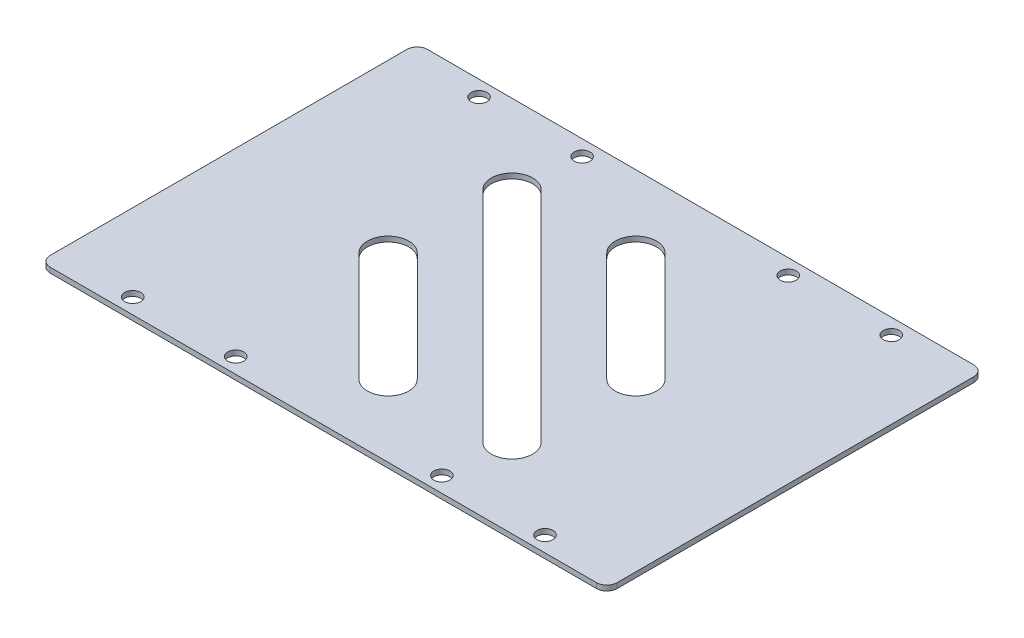
SolidWorks part; units mm, degrees
material "Thornel Mat VMA"
ref_plane "前视基准面" through (0, 0, 0) normal (0, 0, 1) x (1, 0, 0)
ref_plane "上视基准面" through (0, 0, 0) normal (0, 1, 0) x (1, 0, 0)
ref_plane "右视基准面" through (0, 0, 0) normal (1, 0, 0) x (0, 0, -1)
other "Configuration Table"
sketch "草图1" plane through (0, 0, 0) normal (0, 1, 0) x (1, 0, 0)
  line L1 (-55, 36.6) -> (55, 36.6)
  line L2 (-55, 36.6) -> (-55, -36.6)
  line L3 (-55, -36.6) -> (55, -36.6)
  line L4 (55, 36.6) -> (55, -36.6)
  line L5 (-55, 36.6) -> (55, -36.6) construction
  line L6 (-55, -36.6) -> (55, 36.6) construction
  point P0 (0, 0)
  dimension "D1" = 110
  dimension "D2" = 73.2
extrude "凸台-拉伸1" add sketch "草图1" along normal blind 1
sketch "草图2" plane through (0, 1, 0) normal (0, 1, 0) x (1, 0, 0)
  line L5 (55, 36.6) -> (-55, 36.6) construction
  line L7 (55, -36.6) -> (55, 36.6) construction
  line L8 (23.2569, 0) -> (0, 0) construction
  line L9 (0, 0) -> (0, 43.1542) construction
  circle A4 centre (20, 33.6) radius 1.55
  circle A5 centre (40, 33.6) radius 1.55
  circle A6 centre (40, -33.6) radius 1.55
  circle A7 centre (20, -33.6) radius 1.55
  circle A8 centre (-20, -33.6) radius 1.55
  circle A9 centre (-40, -33.6) radius 1.55
  circle A10 centre (-40, 33.6) radius 1.55
  circle A11 centre (-20, 33.6) radius 1.55
  dimension "D3" = 3
  dimension "D1" = 3.1
  dimension "D2" = 20
  dimension "D4" = 15
extrude "切除-拉伸1" cut sketch "草图2" against normal blind 5
sketch "草图3" plane through (0, 1, 0) normal (0, 1, 0) x (1, 0, 0)
  line L0 (55, -36.6) -> (55, 36.6) construction
  line L1 (-50, 29.6) -> (50, 29.6) construction
  line L2 (-50, 29.6) -> (-50, -29.6) construction
  line L3 (-50, -29.6) -> (50, -29.6) construction
  line L4 (50, 29.6) -> (50, -29.6) construction
  line L5 (-50, 29.6) -> (50, -29.6) construction
  line L6 (-50, -29.6) -> (50, 29.6) construction
  line L7 (47, 16.6) -> (38.609, 26.6) construction
  line L8 (44.7019, 14.6716) -> (36.3109, 24.6716)
  line L9 (49.2981, 18.5284) -> (40.9071, 28.5284)
  line L10 (47, 1.0428) -> (25.5549, 26.6) construction
  line L11 (44.7019, -0.8856) -> (23.2568, 24.6716)
  line L12 (49.2981, 2.9711) -> (27.8531, 28.5284)
  line L13 (47, -14.5145) -> (12.5009, 26.6) construction
  line L14 (44.7019, -16.4428) -> (10.2027, 24.6716)
  line L15 (49.2981, -12.5861) -> (14.799, 28.5284)
  line L16 (44.0869, -26.6) -> (-0.5532, 26.6) construction
  line L17 (41.7888, -28.5284) -> (-2.8513, 24.6716)
  line L18 (46.385, -24.6716) -> (1.7449, 28.5284)
  line L19 (31.0328, -26.6) -> (-13.6073, 26.6) construction
  line L20 (28.7347, -28.5284) -> (-15.9054, 24.6716)
  line L21 (33.3309, -24.6716) -> (-11.3092, 28.5284)
  line L22 (17.9787, -26.6) -> (-26.6614, 26.6) construction
  line L23 (15.6806, -28.5284) -> (-28.9595, 24.6716)
  line L24 (20.2769, -24.6716) -> (-24.3632, 28.5284)
  line L25 (4.9247, -26.6) -> (-39.7154, 26.6) construction
  line L26 (2.6265, -28.5284) -> (-42.0136, 24.6716)
  line L27 (7.2228, -24.6716) -> (-37.4173, 28.5284)
  line L28 (-34.2376, -26.6) -> (-47, -11.3903) construction
  line L29 (-36.5357, -28.5284) -> (-49.2981, -13.3187)
  line L30 (-31.9394, -24.6716) -> (-44.7019, -9.4619)
  line L31 (-21.1835, -26.6) -> (-47, 4.1669) construction
  line L32 (-23.4816, -28.5284) -> (-49.2981, 2.2386)
  line L33 (-18.8853, -24.6716) -> (-44.7019, 6.0953)
  line L34 (-8.1294, -26.6) -> (-47, 19.7242) construction
  line L35 (-10.4275, -28.5284) -> (-49.2981, 17.7958)
  line L36 (-5.8313, -24.6716) -> (-44.7019, 21.6525)
  circle A0 centre (40, -33.6) radius 1.55 construction
  arc A1 (44.7019, 14.6716) -> (49.2981, 18.5284) centre (47, 16.6) ccw
  arc A2 (40.9071, 28.5284) -> (36.3109, 24.6716) centre (38.609, 26.6) ccw
  arc A3 (44.7019, -0.8856) -> (49.2981, 2.9711) centre (47, 1.0428) ccw
  arc A4 (27.8531, 28.5284) -> (23.2568, 24.6716) centre (25.5549, 26.6) ccw
  arc A5 (44.7019, -16.4428) -> (49.2981, -12.5861) centre (47, -14.5145) ccw
  arc A6 (14.799, 28.5284) -> (10.2027, 24.6716) centre (12.5009, 26.6) ccw
  arc A7 (41.7888, -28.5284) -> (46.385, -24.6716) centre (44.0869, -26.6) ccw
  arc A8 (1.7449, 28.5284) -> (-2.8513, 24.6716) centre (-0.5532, 26.6) ccw
  arc A9 (28.7347, -28.5284) -> (33.3309, -24.6716) centre (31.0328, -26.6) ccw
  arc A10 (-11.3092, 28.5284) -> (-15.9054, 24.6716) centre (-13.6073, 26.6) ccw
  arc A11 (15.6806, -28.5284) -> (20.2769, -24.6716) centre (17.9787, -26.6) ccw
  arc A12 (-24.3632, 28.5284) -> (-28.9595, 24.6716) centre (-26.6614, 26.6) ccw
  arc A13 (2.6265, -28.5284) -> (7.2228, -24.6716) centre (4.9247, -26.6) ccw
  arc A14 (-37.4173, 28.5284) -> (-42.0136, 24.6716) centre (-39.7154, 26.6) ccw
  arc A15 (-36.5357, -28.5284) -> (-31.9394, -24.6716) centre (-34.2376, -26.6) ccw
  arc A16 (-44.7019, -9.4619) -> (-49.2981, -13.3187) centre (-47, -11.3903) ccw
  arc A17 (-23.4816, -28.5284) -> (-18.8853, -24.6716) centre (-21.1835, -26.6) ccw
  arc A18 (-44.7019, 6.0953) -> (-49.2981, 2.2386) centre (-47, 4.1669) ccw
  arc A19 (-10.4275, -28.5284) -> (-5.8313, -24.6716) centre (-8.1294, -26.6) ccw
  arc A20 (-44.7019, 21.6525) -> (-49.2981, 17.7958) centre (-47, 19.7242) ccw
  point P0 (0, 0)
  point P12 (42.8045, 21.6)
  point P17 (36.2775, 13.8214)
  point P24 (29.7504, 6.0428)
  point P31 (21.7668, 0)
  point P39 (8.7128, 0)
  point P46 (-4.3413, 0)
  point P53 (-17.3954, 0)
  point P61 (-40.6188, -18.9952)
  point P66 (-34.0917, -11.2165)
  point P73 (-27.5647, -3.4379)
  dimension "D4" = 3
  dimension "D1" = 4
  dimension "D2" = 5
  dimension "D3" = 50
  dimension "D5" = 10
  dimension "D6" = 10
  dimension "D7" = 10
  dimension "D8" = 10
  dimension "D10" = 10
  dimension "D11" = 10
  dimension "D12" = 10
  dimension "D13" = 10
  dimension "D9" = 4
extrude "切除-拉伸3" [suppressed] cut sketch "草图3" against normal blind 2
fillet "圆角1" radius 2 4 edges at (-55, 0.5, 36.6) (-55, 0.5, -36.6) (55, 0.5, -36.6) (55, 0.5, 36.6)
sketch "草图4" plane through (0, 1, 0) normal (0, 1, 0) x (1, 0, 0)
  line L0 (-21.2132, 21.2132) -> (21.2132, -21.2132) construction
  line L1 (-18.3848, 24.0416) -> (24.0416, -18.3848)
  line L2 (-24.0416, 18.3848) -> (18.3848, -24.0416)
  line L3 (1.4142, 22.6274) -> (22.6274, 1.4142) construction
  line L4 (4.2426, 25.4558) -> (25.4558, 4.2426)
  line L5 (-1.4142, 19.799) -> (19.799, -1.4142)
  line L6 (-53, -36.6) -> (53, -36.6) construction
  line L7 (12.0208, 12.0208) -> (0, 0) construction
  line L8 (0, 0) -> (44.3591, -44.3591) construction
  line L9 (-22.6274, -1.4142) -> (-1.4142, -22.6274) construction
  line L10 (-25.4558, -4.2426) -> (-4.2426, -25.4558)
  line L11 (-19.799, 1.4142) -> (1.4142, -19.799)
  arc A0 (-18.3848, 24.0416) -> (-24.0416, 18.3848) centre (-21.2132, 21.2132) ccw
  arc A1 (18.3848, -24.0416) -> (24.0416, -18.3848) centre (21.2132, -21.2132) ccw
  arc A2 (4.2426, 25.4558) -> (-1.4142, 19.799) centre (1.4142, 22.6274) ccw
  arc A3 (19.799, -1.4142) -> (25.4558, 4.2426) centre (22.6274, 1.4142) ccw
  arc A4 (-25.4558, -4.2426) -> (-19.799, 1.4142) centre (-22.6274, -1.4142) cw
  arc A5 (1.4142, -19.799) -> (-4.2426, -25.4558) centre (-1.4142, -22.6274) cw
  point P2 (0, 0)
  point P9 (12.0208, 12.0208)
  point P22 (-12.0208, -12.0208)
  dimension "D3" = 4
  dimension "D1" = 45
  dimension "D2" = 60
  dimension "D4" = 9
  dimension "D5" = 30
extrude "切除-拉伸4" cut sketch "草图4" against normal blind 10
